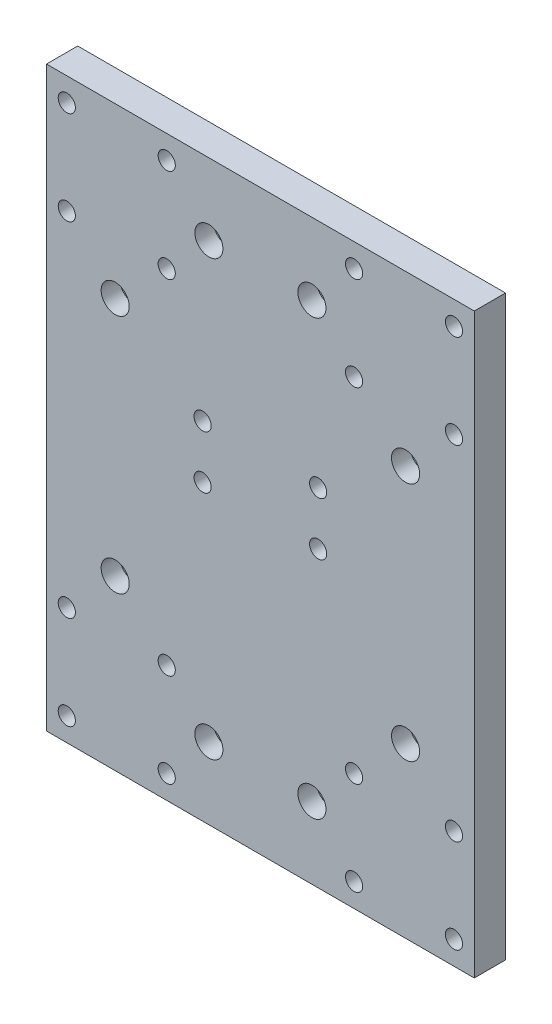
SolidWorks part; units mm, degrees
material "1.0037 (S235JR)"
ref_plane "Płaszczyzna przednia" through (0, 0, 0) normal (0, 0, 1) x (1, 0, 0)
ref_plane "Płaszczyzna górna" through (0, 0, 0) normal (0, 1, 0) x (1, 0, 0)
ref_plane "Płaszczyzna prawa" through (0, 0, 0) normal (1, 0, 0) x (0, 0, -1)
sketch "Szkic1" plane through (0, 0, 0) normal (0, 0, 1) x (1, 0, 0)
  line L8 (0, 185) -> (0, 0)
  line L9 (0, 0) -> (137, 0)
  line L10 (137, 0) -> (137, 185)
  line L11 (137, 185) -> (0, 185)
  dimension "D2" = 137
  dimension "D1" = 185
extrude "Dodanie-wyciągnięcie1" add sketch "Szkic1" along normal blind 10
sketch "Szkic2" plane through (0, 0, 0) normal (0, 0, -1) x (-1, 0, 0)
  circle A0 centre (-6.5, 177.5) radius 2.5 construction
  circle A1 centre (-6.5, 147.5) radius 2.5 construction
  circle A2 centre (-38.5, 177.5) radius 2.5 construction
  circle A3 centre (-38.5, 147.5) radius 2.5 construction
  circle A4 centre (-38.5, 37.5) radius 2.5 construction
  circle A5 centre (-6.5, 37.5) radius 2.5 construction
  circle A6 centre (-6.5, 7.5) radius 2.5 construction
  circle A7 centre (-38.5, 7.5) radius 2.5 construction
  circle A8 centre (-6.5, 177.5) radius 2.5
  circle A9 centre (-6.5, 147.5) radius 2.5
  circle A10 centre (-38.5, 177.5) radius 2.5
  circle A11 centre (-38.5, 147.5) radius 2.5
  circle A12 centre (-38.5, 37.5) radius 2.5
  circle A13 centre (-6.5, 37.5) radius 2.5
  circle A14 centre (-6.5, 7.5) radius 2.5
  circle A15 centre (-38.5, 7.5) radius 2.5
hole_wizard "Pogłębienie walcowe pod M5 Wkręt do części metalowych z łbem sześciokątnym1" positions "Szkic4" profile "Szkic3" counterbore size "M5" standard "Ansi Metryczny" end condition through all
sketch "Szkic4" plane through (0, 0, 0) normal (0, 0, -1) x (-1, 0, 0)
  line L0 (-68.5, 185) -> (-68.5, 0) construction
  line L1 (-137, 185) -> (0, 185) construction
  line L2 (0, 0) -> (-137, 0) construction
  point P1 (-38.5, 177.5)
  point P4 (-6.5, 177.5)
  point P7 (-38.5, 147.5)
  point P10 (-6.5, 147.5)
  point P13 (-38.5, 37.5)
  point P16 (-6.5, 37.5)
  point P19 (-38.5, 7.5)
  point P22 (-6.5, 7.5)
  point P35 (-130.5, 7.5)
  point P36 (-98.5, 7.5)
  point P37 (-130.5, 37.5)
  point P38 (-98.5, 37.5)
  point P39 (-130.5, 147.5)
  point P40 (-98.5, 147.5)
  point P41 (-130.5, 177.5)
  point P42 (-98.5, 177.5)
sketch "Szkic3" plane through (38.5, 177.5, 0) normal (1, 0, 0) x (0, 1, 0)
  line L0 (0, 0) -> (0, 10)
  line L1 (0, 10) -> (2.75, 10)
  line L3 (2.75, 10) -> (2.75, 6)
  line L4 (2.75, 6) -> (4.5, 6)
  line L5 (4.5, 6) -> (4.5, 0)
  line L7 (4.5, 0) -> (0, 0)
  line L11 (0, -6.35) -> (0, 107.95) construction
  dimension "Średnica otworu na wylot" = 5.5
  dimension "Głębokość otworu na wylot" = 10
  dimension "Średnica pogłębienia walcowego" = 9
  dimension "Głębokość pogłębienia walcowego" = 6
hole_wizard "Pogłębienie walcowe pod M5 Wkręt do części metalowych z łbem sześciokątnym2" positions "Szkic6" profile "Szkic5" counterbore size "M5" standard "Ansi Metryczny" end condition through all
sketch "Szkic6" plane through (0, 0, 10) normal (0, 0, 1) x (1, 0, 0)
  line L0 (68.5, 185) -> (68.5, 0) construction
  line L1 (137, 185) -> (0, 185) construction
  line L2 (0, 0) -> (137, 0) construction
  line L4 (0, 185) -> (0, 0) construction
  point P0 (52, 162)
  point P3 (22, 131)
  point P5 (22, 54)
  point P7 (52, 23)
  point P24 (85, 23)
  point P25 (115, 54)
  point P26 (115, 131)
  point P27 (85, 162)
  dimension "D1" = 23
  dimension "D2" = 52
  dimension "D3" = 23
  dimension "D4" = 22
  dimension "D5" = 54
  dimension "D6" = 54
sketch "Szkic5" plane through (52, 162, 10) normal (1, 0, 0) x (0, -1, 0)
  line L0 (0, 0) -> (0, 10)
  line L1 (0, 10) -> (2.75, 10)
  line L3 (2.75, 10) -> (2.75, 6)
  line L4 (2.75, 6) -> (4.5, 6)
  line L5 (4.5, 6) -> (4.5, 0)
  line L7 (4.5, 0) -> (0, 0)
  line L11 (0, -6.35) -> (0, 107.95) construction
  dimension "Średnica otworu na wylot" = 5.5
  dimension "Głębokość otworu na wylot" = 10
  dimension "Średnica pogłębienia walcowego" = 9
  dimension "Głębokość pogłębienia walcowego" = 6
hole_wizard "Pogłębienie walcowe pod M5 Wkręt do części metalowych z łbem sześciokątnym4" positions "Szkic9" profile "Szkic8" counterbore size "M5" standard "Ansi Metric" end condition through all
sketch "Szkic9" plane through (0, 0, 0) normal (0, 0, -1) x (-1, 0, 0)
  point P0 (-87, 111)
  point P2 (-50, 111)
  point P4 (-87, 94)
  point P6 (-50, 94)
sketch "Szkic8" plane through (87, 111, 0) normal (1, 0, 0) x (0, 1, 0)
  line L0 (0, 0) -> (0, 10)
  line L1 (0, 10) -> (2.75, 10)
  line L3 (2.75, 10) -> (2.75, 6)
  line L4 (2.75, 6) -> (4.5, 6)
  line L5 (4.5, 6) -> (4.5, 0)
  line L7 (4.5, 0) -> (0, 0)
  line L11 (0, -6.35) -> (0, 107.95) construction
  dimension "Średnica otworu na wylot" = 5.5
  dimension "Głębokość otworu na wylot" = 10
  dimension "Średnica pogłębienia walcowego" = 9
  dimension "Głębokość pogłębienia walcowego" = 6
equation "\"D3@Szkic6\" = \"D1@Szkic6\""
equation "\"D6@Szkic6\" = \"D5@Szkic6\""
